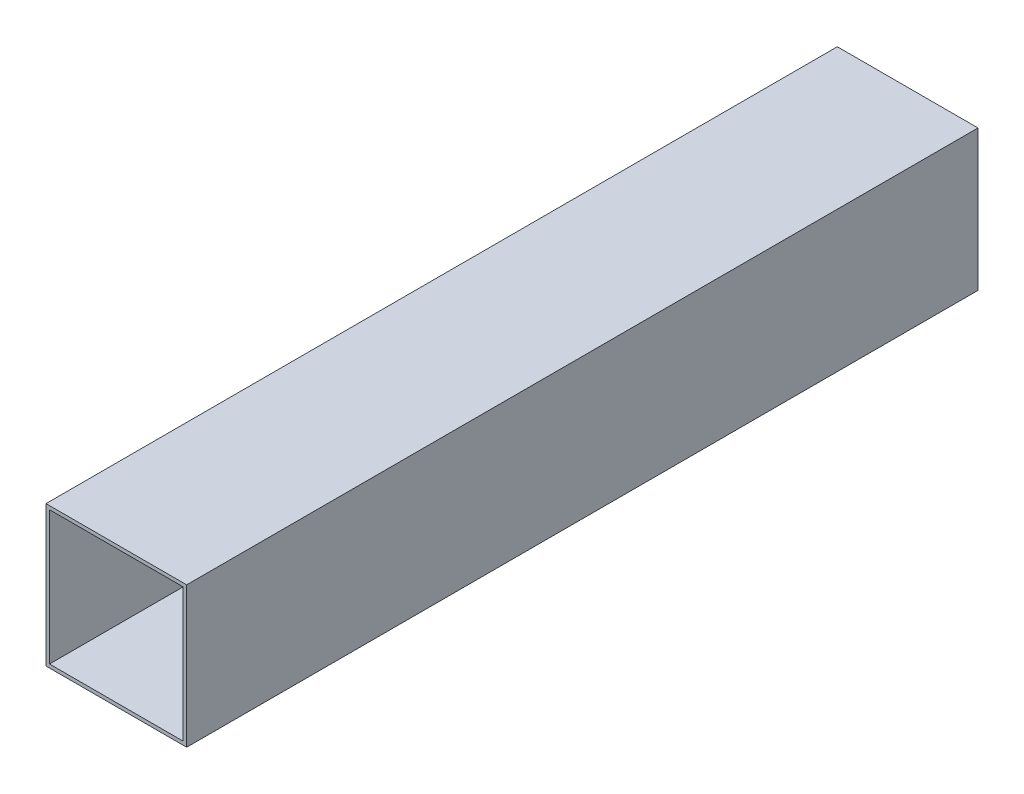
SolidWorks part; units mm, degrees
material "2014-T6"
ref_plane "前视基准面" through (0, 0, 0) normal (0, 0, 1) x (1, 0, 0)
ref_plane "上视基准面" through (0, 0, 0) normal (0, 1, 0) x (1, 0, 0)
ref_plane "右视基准面" through (0, 0, 0) normal (1, 0, 0) x (0, 0, -1)
other "Configuration Table"
sketch "草图1" plane through (0, 0, 0) normal (0, 0, 1) x (1, 0, 0)
  line L1 (0, 0) -> (40, 0)
  line L2 (0, 0) -> (0, 40)
  line L3 (0, 40) -> (40, 40)
  line L4 (40, 0) -> (40, 40)
  line L5 (1, 1) -> (39, 1)
  line L6 (1, 1) -> (1, 39)
  line L7 (1, 39) -> (39, 39)
  line L8 (39, 1) -> (39, 39)
  dimension "D1" = 40
  dimension "D2" = 40
  dimension "D3" = 1
  dimension "D4" = 1
  dimension "D5" = 1
  dimension "D6" = 1
extrude "凸台-拉伸1" add sketch "草图1" along normal blind 225
